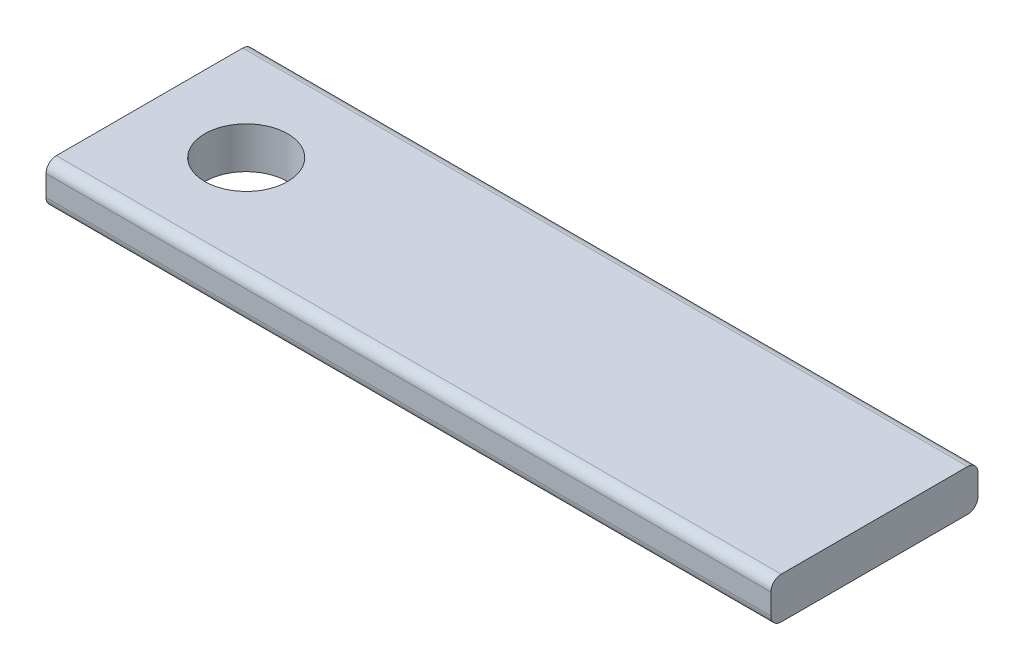
SolidWorks part; units mm, degrees
ref_plane "正面" through (0, 0, 0) normal (0, 0, 1) x (1, 0, 0)
ref_plane "平面" through (0, 0, 0) normal (0, 1, 0) x (1, 0, 0)
ref_plane "右側面" through (0, 0, 0) normal (1, 0, 0) x (0, 0, -1)
sketch "ｽｹｯﾁ1" plane through (0, 0, 0) normal (0, 1, 0) x (1, 0, 0)
  line L1 (-26.25, -7.5) -> (26.25, -7.5)
  line L2 (-26.25, -7.5) -> (-26.25, 7.5)
  line L3 (-26.25, 7.5) -> (26.25, 7.5)
  line L4 (26.25, -7.5) -> (26.25, 7.5)
  line L5 (-26.25, -7.5) -> (26.25, 7.5) construction
  line L6 (-26.25, 7.5) -> (26.25, -7.5) construction
  point P0 (0, 0)
  dimension "D1" = 15
  dimension "D2" = 52.5
extrude "ﾎﾞｽ - 押し出し1" add sketch "ｽｹｯﾁ1" along normal mid plane 3
fillet "ﾌｨﾚｯﾄ1" radius 0.75 4 edges at (0, -1.5, -7.5) (0, 1.5, -7.5) (0, -1.5, 7.5) (0, 1.5, 7.5)
sketch "ｽｹｯﾁ2" plane through (0, 1.5, 0) normal (0, 1, 0) x (1, 0, 0)
  line L0 (-26.25, 0) -> (-19.25, 0) construction
  line L1 (-26.25, 6.75) -> (-26.25, -6.75) construction
  circle A0 centre (-19.25, 0) radius 3
  dimension "D2" = 6
  dimension "D1" = 7
extrude "ｶｯﾄ - 押し出し1" cut sketch "ｽｹｯﾁ2" against normal blind 3
